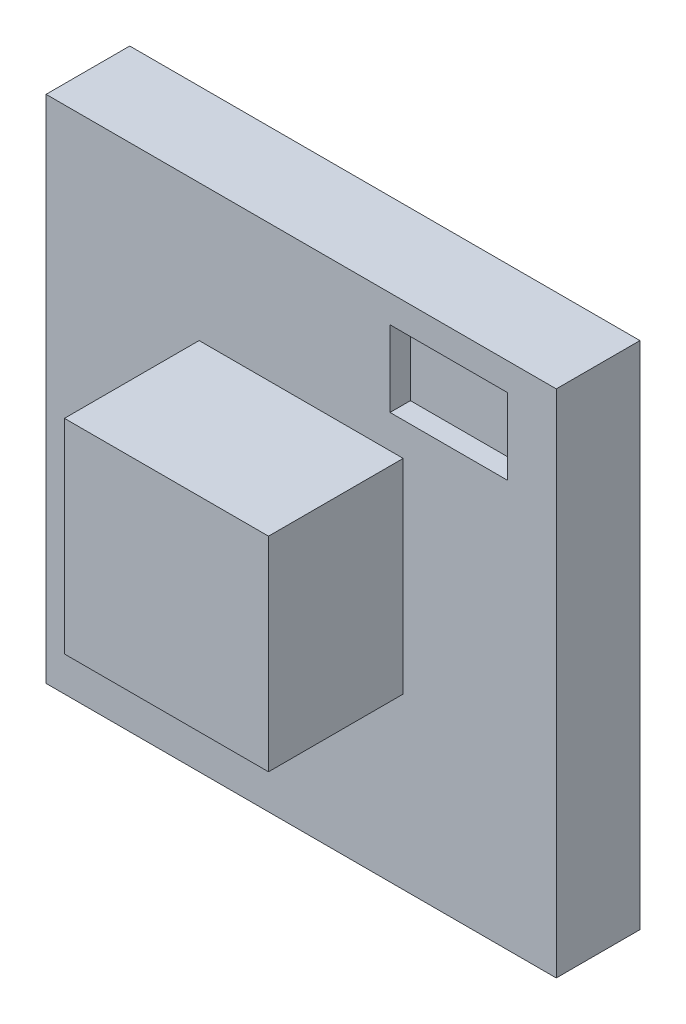
SolidWorks part; units mm, degrees
ref_plane "前视基准面" through (0, 0, 0) normal (0, 0, 1) x (1, 0, 0)
ref_plane "上视基准面" through (0, 0, 0) normal (0, 1, 0) x (1, 0, 0)
ref_plane "右视基准面" through (0, 0, 0) normal (1, 0, 0) x (0, 0, -1)
other "Configuration Table"
sketch "草图1" plane through (0, 0, 0) normal (0, 0, 1) x (1, 0, 0)
  line L1 (-23.8245, 22.1247) -> (1.1755, 22.1247)
  line L2 (-23.8245, 22.1247) -> (-23.8245, -2.8753)
  line L3 (-23.8245, -2.8753) -> (1.1755, -2.8753)
  line L4 (1.1755, 22.1247) -> (1.1755, -2.8753)
  line L5 (-23.8245, 22.1247) -> (1.1755, -2.8753) construction
  line L6 (-23.8245, -2.8753) -> (1.1755, 22.1247) construction
  point P0 (-11.3245, 9.6247)
  dimension "D1" = 25
  dimension "D2" = 25
extrude "凸台-拉伸1" add sketch "草图1" along normal blind 4.1
sketch "草图2" plane through (0, 0, 4.1) normal (0, 0, 1) x (1, 0, 0)
  line L1 (-16.3245, 15.4247) -> (-6.3245, 15.4247)
  line L2 (-16.3245, 15.4247) -> (-16.3245, 5.4247)
  line L3 (-16.3245, 5.4247) -> (-6.3245, 5.4247)
  line L4 (-6.3245, 15.4247) -> (-6.3245, 5.4247)
  line L5 (-16.3245, 15.4247) -> (-6.3245, 5.4247) construction
  line L6 (-16.3245, 5.4247) -> (-6.3245, 15.4247) construction
  line L7 (1.1755, -2.8753) -> (1.1755, 22.1247) construction
  line L8 (1.1755, 22.1247) -> (-23.8245, 22.1247) construction
  point P0 (-11.3245, 10.4247)
  dimension "D1" = 10
  dimension "D2" = 10
  dimension "D3" = 6.7
  dimension "D4" = 7.5
extrude "凸台-拉伸2" add sketch "草图2" along normal blind 6.6
sketch "草图3" plane through (0, 0, 4.1) normal (0, 0, 1) x (1, 0, 0)
  line L1 (-6.9706, 20.7729) -> (-1.2122, 20.7729)
  line L2 (-6.9706, 20.7729) -> (-6.9706, 17.051)
  line L3 (-6.9706, 17.051) -> (-1.2122, 17.051)
  line L4 (-1.2122, 20.7729) -> (-1.2122, 17.051)
  line L5 (-6.9706, 20.7729) -> (-1.2122, 17.051) construction
  line L6 (-6.9706, 17.051) -> (-1.2122, 20.7729) construction
  point P0 (-4.0914, 18.9119)
  point P5 (-4.0914, 18.9119)
extrude "切除-拉伸1" cut sketch "草图3" against normal blind 1
